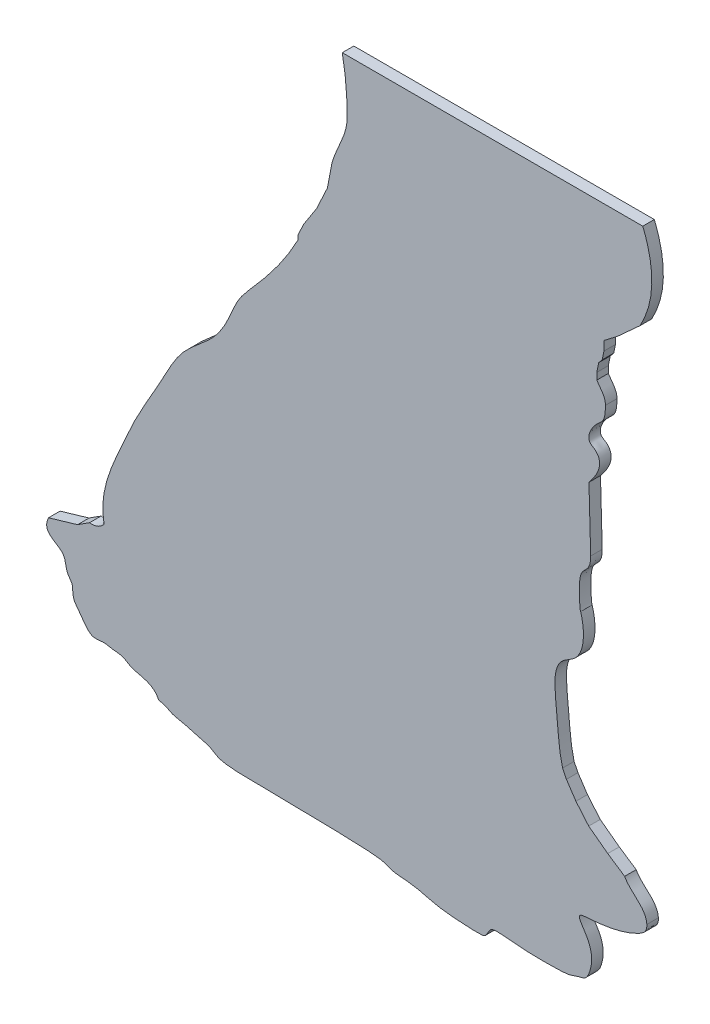
SolidWorks part; units mm, degrees
ref_plane "Front Plane" through (0, 0, 0) normal (0, 0, 1) x (1, 0, 0)
ref_plane "Top Plane" through (0, 0, 0) normal (0, 1, 0) x (1, 0, 0)
ref_plane "Right Plane" through (0, 0, 0) normal (1, 0, 0) x (0, 0, -1)
sketch "Sketch1" plane through (0, 0, 0) normal (0, 0, 1) x (1, 0, 0)
  line L0 (134.6667, 500.5) -> (673.3333, 500.5) construction
  line L2 (167.2022, 42.2012) -> (162.5517, 45.3095)
  line L3 (162.5517, 45.3095) -> (157.3147, 49.2233)
  line L4 (157.3147, 49.2233) -> (153.7929, 53.3936)
  line L5 (153.7929, 53.3936) -> (151.1787, 57.3127)
  line L6 (151.1787, 57.3127) -> (150.1126, 59.4633)
  line L7 (157.3755, 131.2295) -> (157.854, 113.8805)
  line L8 (159.5344, 156.6595) -> (159.5344, 158.498)
  line L9 (159.5344, 158.498) -> (160.0825, 161.1123)
  line L10 (160.0825, 161.1123) -> (161.0243, 162.2425)
  line L11 (161.0243, 162.2425) -> (161.5128, 164.5724)
  line L12 (161.5128, 164.5724) -> (161.5128, 167.1023)
  line L13 (161.5128, 167.1023) -> (165.1835, 169.9013)
  line L14 (165.1835, 169.9013) -> (171.472, 175.6217)
  line L15 (86.5908, 171.7678) -> (85.3882, 165.3811)
  line L16 (89.473, 199.6877) -> (172.1964, 199.6877)
  line L17 (85.3882, 165.3811) -> (82.4023, 158.9826)
  line L18 (82.4023, 158.9826) -> (78.8266, 153.4325)
  line L19 (78.8266, 153.4325) -> (77.3096, 150.1819)
  line L20 (77.3096, 150.1819) -> (77.3096, 148.973)
  line L21 (89.473, 199.6877) -> (189.494, 199.6877) construction
  line L22 (127.4919, 8.5553) -> (214.3131, 8.5553) construction
  line L23 (8.6124, 48.3831) -> (8.6124, -14.4171) construction
  line L24 (173.32, 33.793) -> (173.32, -11.6797) construction
  spline S0 degree 1 poles (8.6124, 48.3831) (16.6111, 50.7357) knots 0 0 1 1
  spline S1 degree 1 poles (19.9047, 52.853) (16.6111, 50.7357) knots 0 0 1 1
  spline S2 degree 3 poles (23.9041, 54.4997) (22.542, 62.0444) (27.1512, 71.7199) (33.1716, 85.6736) (39.4703, 95.7444) (45.0444, 107.3971) (54.1548, 113.0729) (58.3579, 120.6747) (60.6418, 126.7915) (68.4166, 135.2748) (73.9208, 142.4894) (77.3096, 148.973) knots 0 0 0 0 0.194457 0.285904 0.412664 0.517827 0.629269 0.691339 0.750377 0.804905 1 1 1 1
  spline S3 degree 2 poles (19.9047, 52.853) (22.4371, 52.6083) (23.9041, 54.4997) knots 0 0 0 1 1 1
  spline S4 degree 3 poles (8.6124, 48.3831) (6.5691, 43.9628) (13.6478, 43.7296) (13.2535, 37.9915) (15.2259, 36.1128) (15.2445, 34.2074) (15.4257, 32.4092) (16.9812, 30.3171) (18.455, 28.2086) (20.7273, 25.6089) (23.6404, 26.5196) (26.3788, 25.705) (29.0077, 25.795) (31.226, 24.0079) (34.9468, 23.3493) (38.0007, 22.2222) (38.8831, 20.145) knots 0 0 0 0 0.18572 0.273851 0.320038 0.350192 0.393849 0.435551 0.514834 0.569195 0.638874 0.687587 0.755837 0.801068 0.865551 1 1 1 1
  spline S5 degree 3 poles (38.8831, 20.145) (41.2875, 19.5656) (42.3458, 18.5073) (45.4199, 18.1546) (49.7538, 16.7939) (52.7775, 16.1892) (54.7934, 14.8285) (56.3556, 14.1734) (60.1352, 13.7702) (61.5463, 13.7702) (99.2418, 13.2159) (101.2856, 12.2232) (103.9594, 11.2977) (106.3246, 11.2977) (111.5693, 10.5778) (115.1686, 9.2409) (123.9098, 8.5211) (128.0233, 8.5211) (128.9488, 8.7267) (129.9772, 10.7835) (131.0055, 11.8119) (139.3353, 10.7835) (144.7857, 10.7835) (151.9843, 10.7835) (154.3496, 12.1204) (156.7148, 12.1204) (158.1545, 16.0282) (158.1545, 19.319) (157.3318, 21.6842) (156.4063, 23.3296) (153.7325, 27.1346) (157.3189, 27.1346) (163.0629, 27.7755) (167.4392, 28.9243) (170.3933, 30.1004) (172.4447, 31.2857) (173.2037, 32.3228) (173.32, 33.1913) (173.32, 33.793) knots 0 0 0 0 0.028571 0.057143 0.085714 0.114286 0.142857 0.171429 0.2 0.228571 0.257143 0.285714 0.314286 0.342857 0.371429 0.4 0.428571 0.457143 0.485714 0.514286 0.542857 0.571429 0.6 0.628571 0.657143 0.685714 0.714286 0.742857 0.771429 0.8 0.828571 0.857143 0.885714 0.914286 0.942857 0.971429 0.985714 1 1 1 1
  spline S6 degree 3 poles (173.32, 33.793) (173.0564, 37.6266) (168.8406, 39.1122) (167.2022, 42.2012) knots 0 0 0 0 1 1 1 1
  spline S7 degree 3 poles (150.1126, 59.4633) (148.9568, 63.837) (148.9486, 71.4394) (146.8505, 84.0514) (156.4694, 88.1502) (156.2475, 95.5102) (155.0853, 99.2556) knots 0 0 0 0 0.308783 0.618237 0.704406 1 1 1 1
  spline S8 degree 3 poles (157.854, 113.8805) (157.8564, 113.8699) (157.8506, 110.688) (155.3081, 109.3846) (154.4188, 105.0533) (154.8696, 99.4834) (155.0853, 99.2556) knots 0 0 0 0 0.124799 0.365608 0.555267 1 1 1 1
  spline S9 degree 3 poles (161.8927, 151.8072) (161.9125, 149.0313) (161.4499, 147.7916) (158.4451, 145.386) (156.1309, 141.3803) (158.8302, 140.0435) (161.6487, 137.4079) (159.4597, 133.7277) (157.3755, 131.2295) knots 0 0 0 0 0.190659 0.228613 0.488803 0.534056 0.585176 1 1 1 1
  spline S10 degree 3 poles (159.5344, 156.6595) (160.7867, 154.8399) (162.0055, 153.6124) (161.8927, 151.8072) knots 0 0 0 0 1 1 1 1
  spline S11 degree 2 poles (172.1964, 199.6877) (177.5125, 186.6119) (171.472, 175.6217) knots 0 0 0 1 1 1
  spline S12 degree 3 poles (89.473, 199.6877) (90.4497, 194.8375) (90.826, 189.8378) (90.8383, 180.2807) (87.6783, 176.1914) (86.5908, 171.7678) knots 0 0 0 0 0.517811 0.520823 1 1 1 1
extrude "Boss-Extrude2" add sketch "Sketch1" along normal blind 3.175
